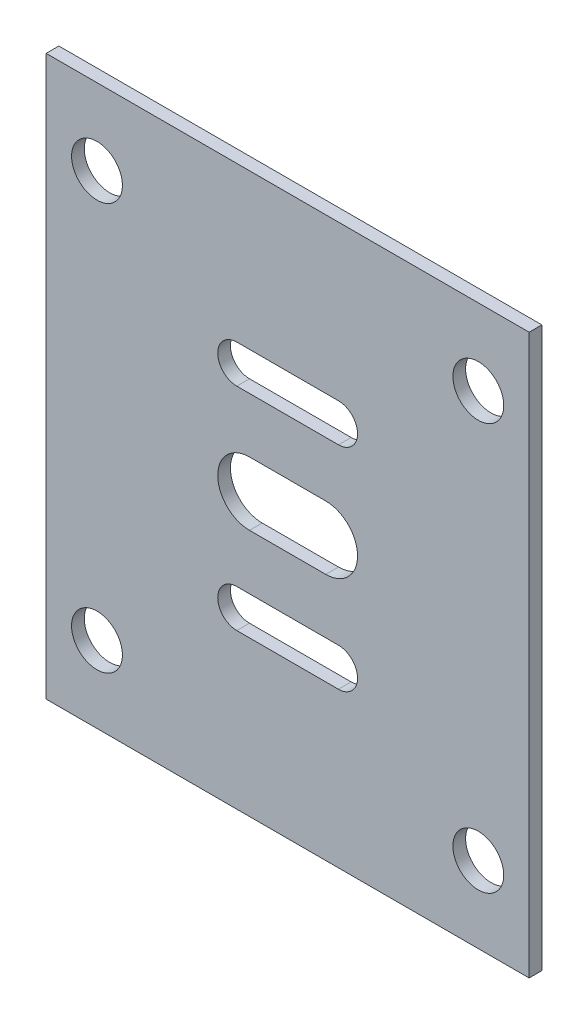
SolidWorks part; units mm, degrees
ref_plane "Front Plane" through (0, 0, 0) normal (0, 0, 1) x (1, 0, 0)
ref_plane "Top Plane" through (0, 0, 0) normal (0, 1, 0) x (1, 0, 0)
ref_plane "Right Plane" through (0, 0, 0) normal (1, 0, 0) x (0, 0, -1)
sketch "Sketch1" plane through (0, 0, 0) normal (0, 0, 1) x (1, 0, 0)
  line L1 (-19, -22) -> (19, -22)
  line L2 (-19, -22) -> (-19, 22)
  line L3 (-19, 22) -> (19, 22)
  line L4 (19, -22) -> (19, 22)
  circle A4 centre (-15, 16) radius 2
  circle A5 centre (-15, -16) radius 2
  circle A6 centre (15, -16) radius 2
  circle A7 centre (15, 16) radius 2
  point P0 (0, 0)
  dimension "D1" = 4
  dimension "D2" = 15
  dimension "D3" = 19
  dimension "D4" = 15
  dimension "D5" = 19
  dimension "D6" = 16
  dimension "D7" = 22
  dimension "D8" = 16
  dimension "D9" = 22
extrude "Boss-Extrude1" add sketch "Sketch1" along normal blind 1
sketch "Sketch2" plane through (0, 0, 0) normal (0, 0, 1) x (1, 0, 0)
  line L0 (-3, 0) -> (3, 0) construction
  line L1 (-4, 8.327) -> (4, 8.327) construction
  line L2 (-3, 2.5) -> (3, 2.5)
  line L3 (-3, -2.5) -> (3, -2.5)
  line L6 (-4, 9.827) -> (4, 9.827)
  line L7 (-4, 6.827) -> (4, 6.827)
  line L9 (-4, -8.327) -> (4, -8.327) construction
  line L10 (-4, -9.827) -> (4, -9.827)
  line L11 (-4, -6.827) -> (4, -6.827)
  arc A0 (-3, 2.5) -> (-3, -2.5) centre (-3, 0) ccw
  arc A1 (3, -2.5) -> (3, 2.5) centre (3, 0) ccw
  arc A4 (-4, 9.827) -> (-4, 6.827) centre (-4, 8.327) ccw
  arc A5 (4, 6.827) -> (4, 9.827) centre (4, 8.327) ccw
  arc A6 (-4, -9.827) -> (-4, -6.827) centre (-4, -8.327) cw
  arc A7 (4, -6.827) -> (4, -9.827) centre (4, -8.327) cw
  point P5 (0, 0)
  point P6 (0, 0)
  point P11 (0, 0)
  point P12 (0, 8.327)
  point P21 (0, -8.327)
  dimension "D1" = 2.5
  dimension "D2" = 1.5
  dimension "D3" = 3
  dimension "D4" = 4
  dimension "D5" = 8.327
  dimension "D6" = 8.327
extrude "Cut-Extrude1" cut sketch "Sketch2" along normal through all both and the other way through all
